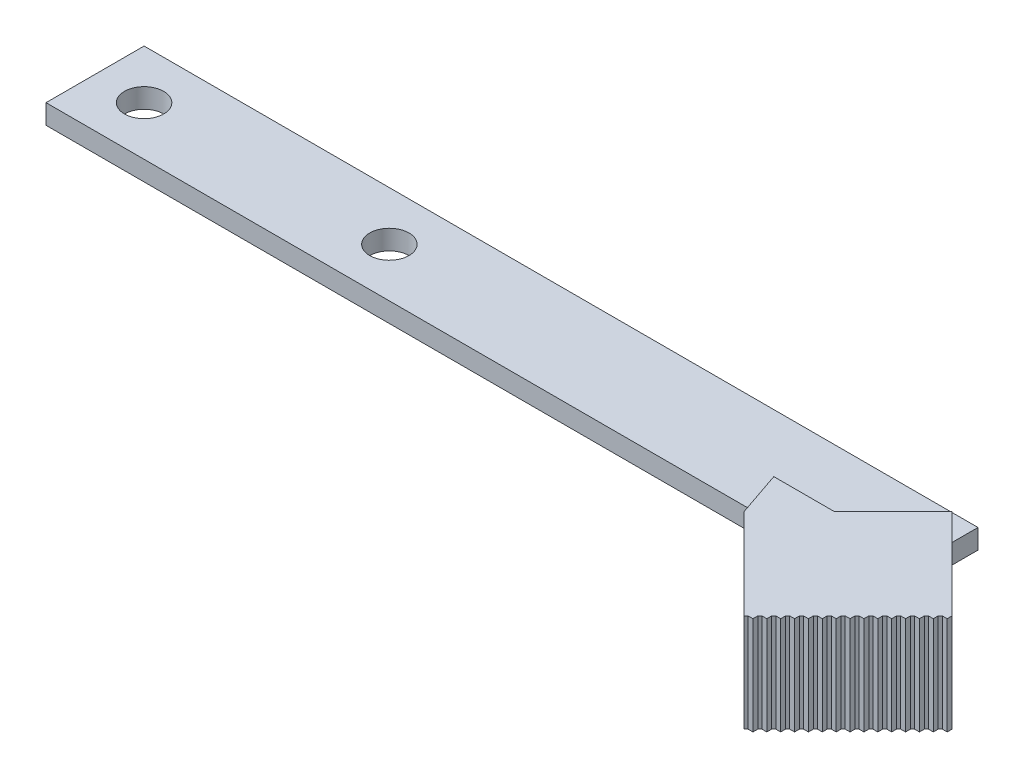
SolidWorks part; units mm, degrees
material "1060 Alloy"
ref_plane "Front Plane" through (0, 0, 0) normal (0, 0, 1) x (1, 0, 0)
ref_plane "Top Plane" through (0, 0, 0) normal (0, 1, 0) x (1, 0, 0)
ref_plane "Right Plane" through (0, 0, 0) normal (1, 0, 0) x (0, 0, -1)
sketch "Sketch1" plane through (0, 0, 0) normal (0, 1, 0) x (1, 0, 0)
  line L1 (-24.2292, 7.0539) -> (60.7708, 7.0539)
  line L2 (-24.2292, 7.0539) -> (-24.2292, -2.9461)
  line L3 (-24.2292, -2.9461) -> (60.7708, -2.9461)
  line L4 (60.7708, 7.0539) -> (60.7708, -2.9461)
  circle A0 centre (-19.2292, 2.0539) radius 2
  circle A2 centre (5.7708, 2.0539) radius 2
  dimension "D3" = 5
  dimension "D5" = 25
  dimension "D1" = 10
  dimension "D2" = 85
extrude "Boss-Extrude1" add sketch "Sketch1" along normal blind 2
sketch "Sketch2" plane through (0, 2, 0) normal (0, 1, 0) x (1, 0, 0)
  line L0 (60.7708, 2.0539) -> (55.7708, -2.9461)
  line L1 (60.7708, -2.9461) -> (60.7708, 7.0539) construction
  line L2 (-24.2292, -2.9461) -> (60.7708, -2.9461) construction
  line L3 (60.7708, 2.0539) -> (60.7708, -2.9461)
  line L4 (60.7708, -2.9461) -> (55.7708, -2.9461)
  dimension "D1" = 135
extrude "Cut-Extrude1" cut sketch "Sketch2" against normal blind 10
sketch "Sketch3" plane through (29.3584, 0, 29.3584) normal (0.7071, 0, 0.7071) x (0.7071, 0, -0.7071)
  line L1 (46.0903, -4.1117) -> (31.0903, -4.1117)
  line L2 (46.0903, -4.1117) -> (46.0903, 5.8883)
  line L3 (46.0903, 5.8883) -> (31.0903, 5.8883)
  line L4 (31.0903, -4.1117) -> (31.0903, 5.8883)
  dimension "D1" = 15
  dimension "D2" = 10
extrude "Boss-Extrude2" add sketch "Sketch3" along normal blind 13
sketch "Sketch4" plane through (0, 5.8883, 0) normal (0, 1, 0) x (1, 0, 0)
  line L0 (51.3426, -7.3743) -> (49.7625, -2.7526)
  line L1 (49.7625, -2.7526) -> (55.9643, -2.7526)
  line L2 (61.9492, 3.2324) -> (51.3426, -7.3743) construction
  line L3 (55.9643, -2.7526) -> (51.3426, -7.3743)
extrude "Boss-Extrude3" add sketch "Sketch4" against normal blind 10
sketch "Sketch5" plane through (0, 5.8883, 0) normal (0, 1, 0) x (1, 0, 0)
  line L0 (71.1416, -5.96) -> (71.1416, -6.46)
  line L1 (71.1416, -6.46) -> (70.6416, -6.46)
  line L2 (71.1416, -5.96) -> (60.535, -16.5666) construction
  line L3 (70.6416, -6.46) -> (71.1416, -5.96)
  line L4 (70.4345, -6.6671) -> (70.4345, -7.1671)
  line L5 (70.4345, -7.1671) -> (69.9345, -7.1671)
  line L6 (69.9345, -7.1671) -> (70.4345, -6.6671)
  line L7 (69.7274, -7.3743) -> (69.7274, -7.8743)
  line L8 (69.7274, -7.8743) -> (69.2274, -7.8743)
  line L9 (69.2274, -7.8743) -> (69.7274, -7.3743)
  line L10 (69.0203, -8.0814) -> (69.0203, -8.5814)
  line L11 (69.0203, -8.5814) -> (68.5203, -8.5814)
  line L12 (68.5203, -8.5814) -> (69.0203, -8.0814)
  line L13 (68.3132, -8.7885) -> (68.3132, -9.2885)
  line L14 (68.3132, -9.2885) -> (67.8132, -9.2885)
  line L15 (67.8132, -9.2885) -> (68.3132, -8.7885)
  line L16 (67.6061, -9.4956) -> (67.6061, -9.9956)
  line L17 (67.6061, -9.9956) -> (67.1061, -9.9956)
  line L18 (67.1061, -9.9956) -> (67.6061, -9.4956)
  line L19 (66.899, -10.2027) -> (66.899, -10.7027)
  line L20 (66.899, -10.7027) -> (66.399, -10.7027)
  line L21 (66.399, -10.7027) -> (66.899, -10.2027)
  line L22 (66.1919, -10.9098) -> (66.1919, -11.4098)
  line L23 (66.1919, -11.4098) -> (65.6919, -11.4098)
  line L24 (65.6919, -11.4098) -> (66.1919, -10.9098)
  line L25 (65.4848, -11.6169) -> (65.4848, -12.1169)
  line L26 (65.4848, -12.1169) -> (64.9848, -12.1169)
  line L27 (64.9848, -12.1169) -> (65.4848, -11.6169)
  line L28 (64.7777, -12.324) -> (64.7777, -12.824)
  line L29 (64.7777, -12.824) -> (64.2777, -12.824)
  line L30 (64.2777, -12.824) -> (64.7777, -12.324)
  line L31 (64.0706, -13.0311) -> (64.0706, -13.5311)
  line L32 (64.0706, -13.5311) -> (63.5706, -13.5311)
  line L33 (63.5706, -13.5311) -> (64.0706, -13.0311)
  line L34 (63.3634, -13.7382) -> (63.3634, -14.2382)
  line L35 (63.3634, -14.2382) -> (62.8634, -14.2382)
  line L36 (62.8634, -14.2382) -> (63.3634, -13.7382)
  line L37 (62.6563, -14.4453) -> (62.6563, -14.9453)
  line L38 (62.6563, -14.9453) -> (62.1563, -14.9453)
  line L39 (62.1563, -14.9453) -> (62.6563, -14.4453)
  line L40 (61.9492, -15.1524) -> (61.9492, -15.6524)
  line L41 (61.9492, -15.6524) -> (61.4492, -15.6524)
  line L42 (61.4492, -15.6524) -> (61.9492, -15.1524)
  line L43 (61.2421, -15.8595) -> (61.2421, -16.3595)
  line L44 (61.2421, -16.3595) -> (60.7421, -16.3595)
  line L45 (60.7421, -16.3595) -> (61.2421, -15.8595)
  dimension "D1" = 0.5
  dimension "D2" = 0.5
  dimension "D3" = 15
extrude "Boss-Extrude4" add sketch "Sketch5" against normal blind 10
